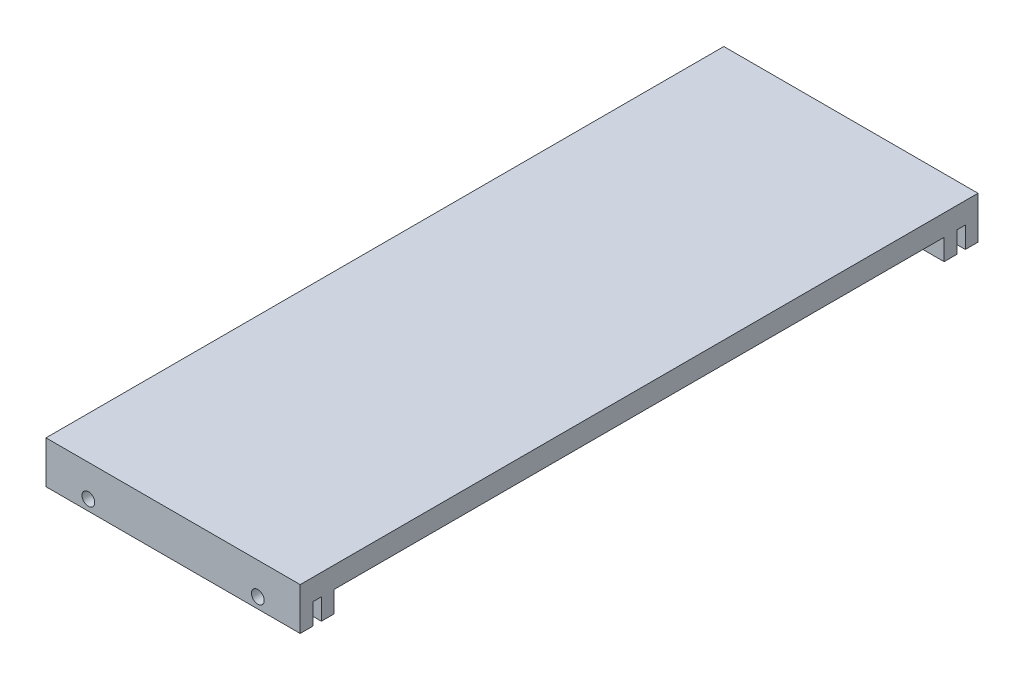
SolidWorks part; units mm, degrees
ref_plane "Front Plane" through (0, 0, 0) normal (0, 0, 1) x (1, 0, 0)
ref_plane "Top Plane" through (0, 0, 0) normal (0, 1, 0) x (1, 0, 0)
ref_plane "Right Plane" through (0, 0, 0) normal (1, 0, 0) x (0, 0, -1)
sketch "Sketch1" plane through (0, 0, 0) normal (1, 0, 0) x (0, 0, -1)
  line L0 (-1208.6331, 0) -> (1208.6331, 0) construction
  line L1 (0, -761.1511) -> (0, 761.1511) construction
  line L2 (-400, 0) -> (400, 0)
  line L8 (-385, -50) -> (-400, -50)
  line L9 (-400, -50) -> (-400, 0)
  line L10 (-385, -50) -> (-385, -25)
  line L11 (-385, -25) -> (-375, -25)
  line L12 (-400, -50) -> (462.8687, -50) construction
  line L13 (-375, -25) -> (-375, -50)
  line L15 (375, -50) -> (375, -25)
  line L16 (375, -25) -> (385, -25)
  line L17 (385, -25) -> (385, -50)
  line L18 (385, -50) -> (400, -50)
  line L19 (400, -50) -> (400, 0)
  line L20 (-375, -50) -> (-360, -50)
  line L21 (-360, -50) -> (-360, -25)
  line L22 (-360, -25) -> (360, -25)
  line L23 (360, -25) -> (360, -50)
  line L24 (360, -50) -> (375, -50)
  point P4 (0, 0)
  point P8 (0, 0)
  point P11 (0, 0)
  dimension "D1" = 800
  dimension "D2" = 15
  dimension "D3" = 10
  dimension "D4" = 10
  dimension "D5" = 15
  dimension "D6" = 50
  dimension "D7" = 25
  dimension "D8" = 0
  dimension "D9" = 15
  dimension "D10" = 0
  dimension "D11" = 15
extrude "Boss-Extrude1" add sketch "Sketch1" along normal blind 300
sketch "Sketch2" plane through (0, 0, 400) normal (0, 0, 1) x (1, 0, 0)
  line L0 (300, 0) -> (300, -50) construction
  line L1 (0, 0) -> (0, -50) construction
  line L2 (300, -50) -> (0, -50) construction
  line L3 (300, -50) -> (0, -50) construction
  circle A0 centre (50, -37.5) radius 7.5
  circle A1 centre (250, -37.5) radius 7.5
  dimension "D2" = 50
  dimension "D3" = 15
  dimension "D4" = 15
  dimension "D5" = 12.5
  dimension "D6" = 12.5
  dimension "D1" = 50
extrude "Cut-Extrude1" cut sketch "Sketch2" against normal through all both and the other way through all
